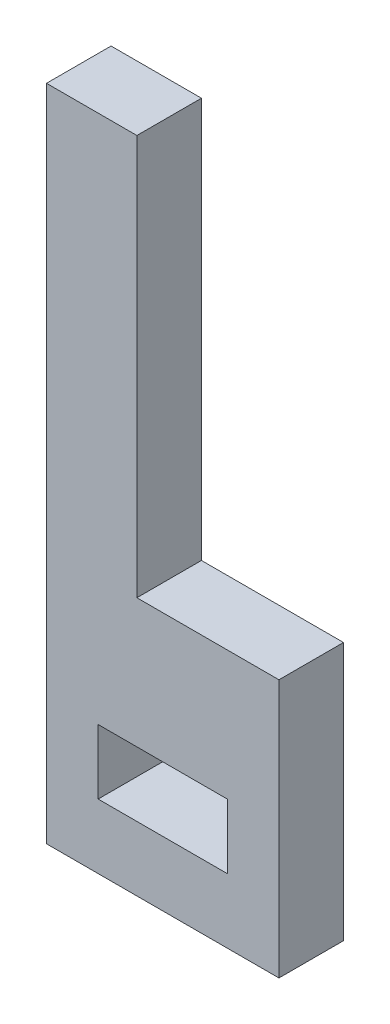
SolidWorks part; units mm, degrees
ref_plane "Front Plane" through (0, 0, 0) normal (0, 0, 1) x (1, 0, 0)
ref_plane "Top Plane" through (0, 0, 0) normal (0, 1, 0) x (1, 0, 0)
ref_plane "Right Plane" through (0, 0, 0) normal (1, 0, 0) x (0, 0, -1)
sketch "Sketch1" plane through (0, 0, 0) normal (0, 0, 1) x (1, 0, 0)
  line L0 (0, 0) -> (0, 51)
  line L1 (0, 51) -> (7, 51)
  line L2 (7, 51) -> (7, 20)
  line L3 (7, 20) -> (18, 20)
  line L4 (18, 20) -> (18, 0)
  line L5 (18, 0) -> (0, 0)
  dimension "D1" = 7
  dimension "D2" = 18
  dimension "D3" = 20
  dimension "D4" = 51
extrude "Boss-Extrude1" add sketch "Sketch1" along normal blind 5
sketch "Sketch2" plane through (0, 0, 5) normal (0, 0, 1) x (1, 0, 0)
  line L0 (0, 0) -> (18, 0) construction
  line L1 (4, 10) -> (14, 10)
  line L2 (4, 10) -> (4, 5)
  line L3 (4, 5) -> (14, 5)
  line L4 (14, 10) -> (14, 5)
  point P6 (9, 10)
  point P7 (9, 0)
  dimension "D1" = 10
  dimension "D2" = 5
  dimension "D3" = 5
extrude "Cut-Extrude1" cut sketch "Sketch2" against normal through all contours L2 L1 L4 L3
